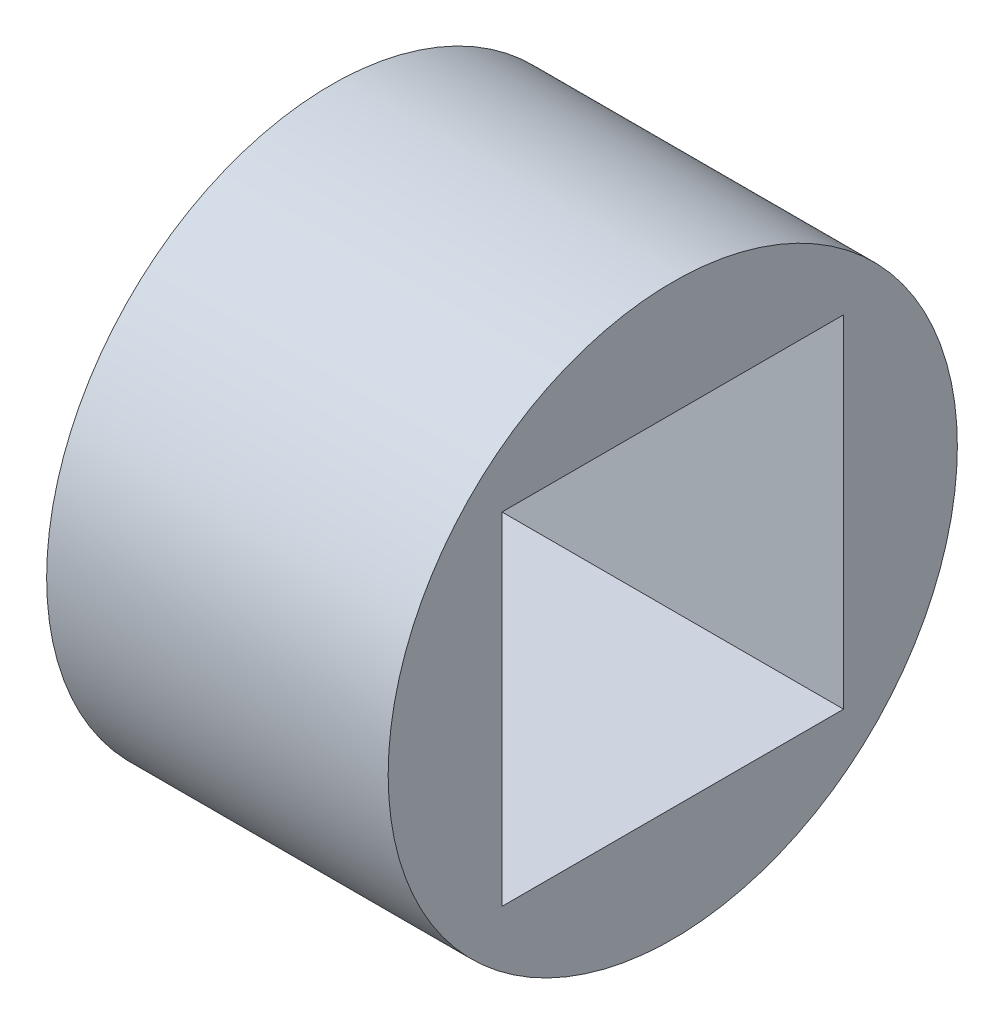
SolidWorks part; units mm, degrees
ref_plane "Front Plane" through (0, 0, 0) normal (0, 0, 1) x (1, 0, 0)
ref_plane "Top Plane" through (0, 0, 0) normal (0, 1, 0) x (1, 0, 0)
ref_plane "Right Plane" through (0, 0, 0) normal (1, 0, 0) x (0, 0, -1)
sketch "Sketch1" plane through (0, 0, 0) normal (1, 0, 0) x (0, 0, -1)
  line L1 (-1.5, -1.5) -> (1.5, -1.5)
  line L2 (-1.5, -1.5) -> (-1.5, 1.5)
  line L3 (-1.5, 1.5) -> (1.5, 1.5)
  line L4 (1.5, -1.5) -> (1.5, 1.5)
  line L5 (-1.5, -1.5) -> (1.5, 1.5) construction
  line L6 (-1.5, 1.5) -> (1.5, -1.5) construction
  circle A0 centre (0, 0) radius 2.5
  dimension "D1" = 5
  dimension "D2" = 3
  dimension "D3" = 3
extrude "Boss-Extrude1" add sketch "Sketch1" along normal blind 3
